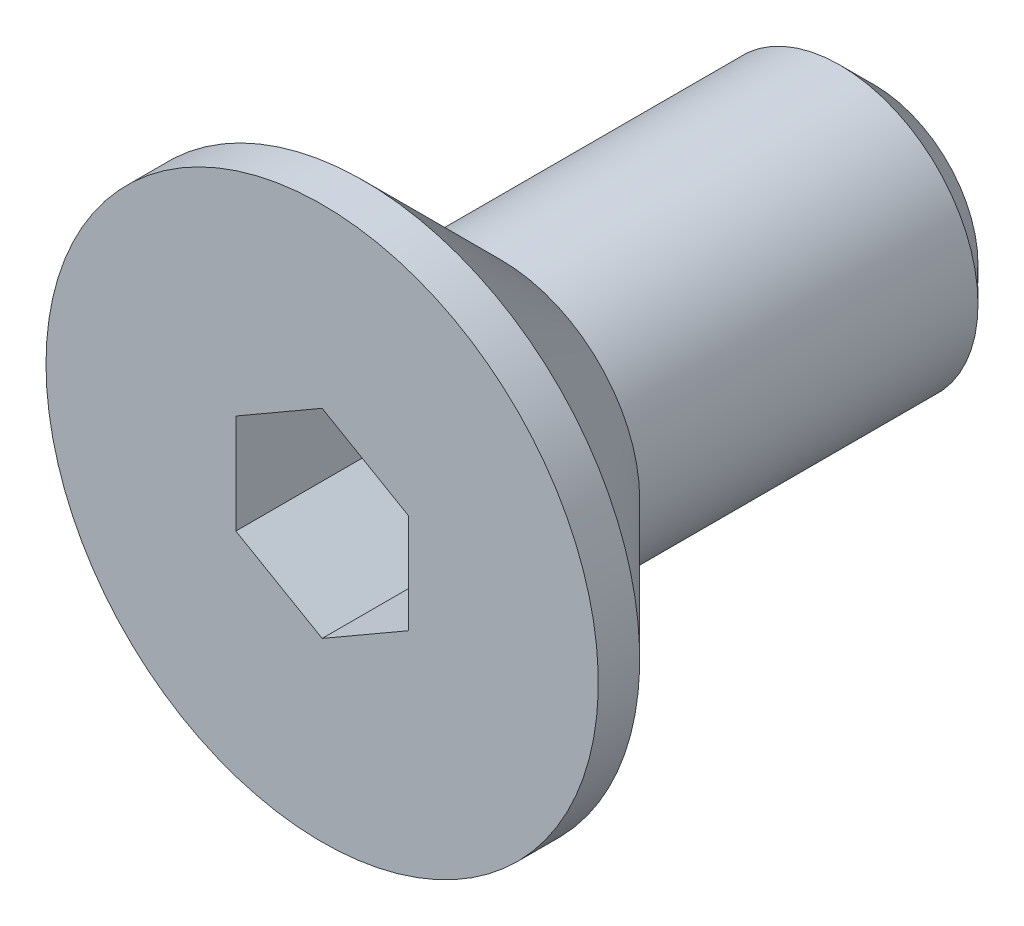
SolidWorks part; units mm, degrees
ref_plane "前视基准面" through (0, 0, 0) normal (0, 0, 1) x (1, 0, 0)
ref_plane "上视基准面" through (0, 0, 0) normal (0, 1, 0) x (1, 0, 0)
ref_plane "右视基准面" through (0, 0, 0) normal (1, 0, 0) x (0, 0, -1)
sketch "草图1" plane through (0, 0, 0) normal (1, 0, 0) x (0, 0, -1)
  line L0 (-4, 0) -> (-4, 4)
  line L1 (-4, 4) -> (-3.4, 4)
  line L2 (-3.4, 4) -> (-1.4, 2)
  line L3 (-1.4, 2) -> (4, 2)
  line L5 (4, 2) -> (4, 0)
  line L6 (4, 0) -> (-4, 0)
  dimension "D1" = 45
  dimension "D2" = 2
  dimension "D3" = 8
  dimension "D4" = 4
  dimension "D5" = 2.6
revolve "旋转1" add sketch "草图1" angle 360 about L6
chamfer "倒角1" distance 0.5 angle 45 1 edges at (-2, 0, -4)
sketch "草图2" plane through (0, 0, 4) normal (0, 0, 1) x (1, 0, 0)
  line L1 (0, 1.4434) -> (-1.25, 0.7217)
  line L2 (-1.25, 0.7217) -> (-1.25, -0.7217)
  line L3 (-1.25, -0.7217) -> (0, -1.4434)
  line L4 (0, -1.4434) -> (1.25, -0.7217)
  line L5 (1.25, -0.7217) -> (1.25, 0.7217)
  line L6 (1.25, 0.7217) -> (0, 1.4434)
  circle A0 centre (0, 0) radius 1.25 construction
  dimension "D1" = 2.5
extrude "切除-拉伸1" cut sketch "草图2" against normal blind 2.5
